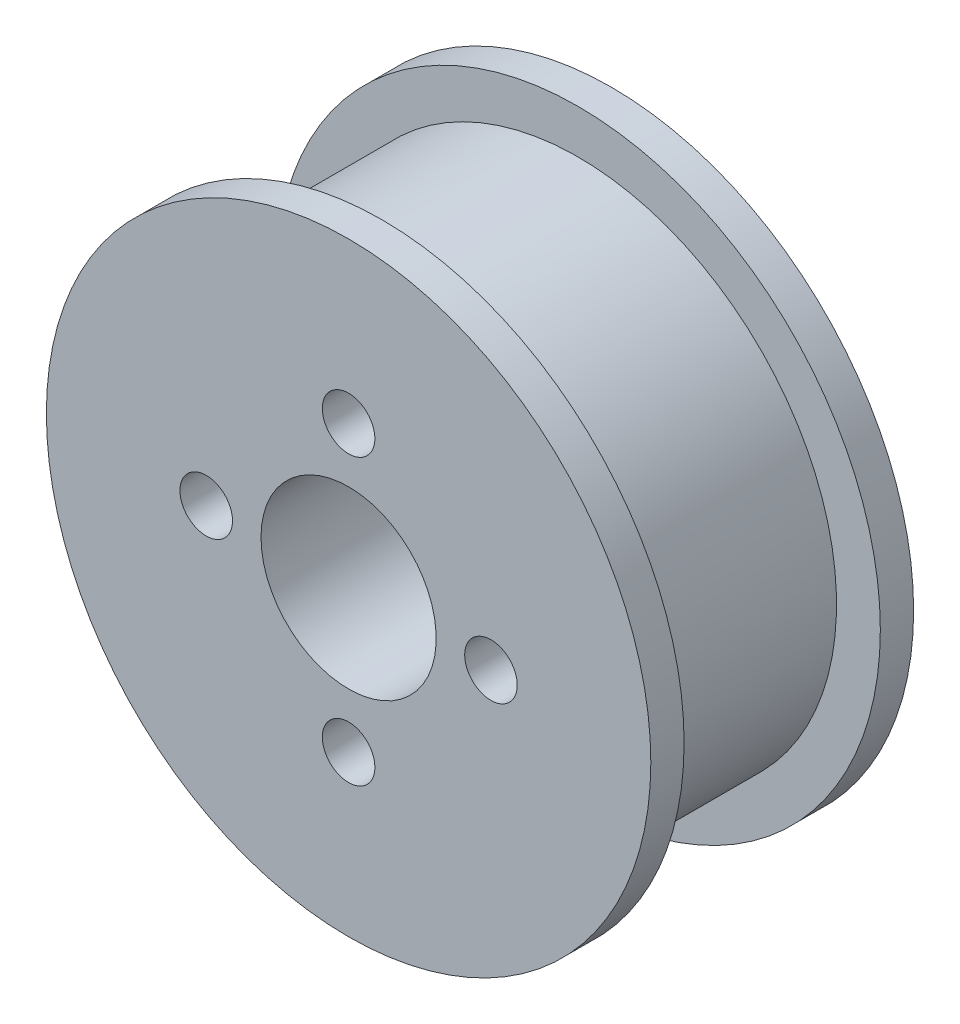
SolidWorks part; units mm, degrees
ref_plane "Front Plane" through (0, 0, 0) normal (0, 0, 1) x (1, 0, 0)
ref_plane "Top Plane" through (0, 0, 0) normal (0, 1, 0) x (1, 0, 0)
ref_plane "Right Plane" through (0, 0, 0) normal (1, 0, 0) x (0, 0, -1)
sketch "Sketch1" plane through (0, 0, 0) normal (0, 0, 1) x (1, 0, 0)
  circle A0 centre (0, 0) radius 17.25
  dimension "D1" = 34.5
extrude "Boss-Extrude1" add sketch "Sketch1" along normal blind 1.9
sketch "Sketch2" plane through (0, 0, 0) normal (0, 0, -1) x (-1, 0, 0)
  circle A0 centre (0, 0) radius 14.75
  dimension "D1" = 29.5
extrude "Boss-Extrude2" add sketch "Sketch2" along normal blind 11.2
sketch "Sketch3" plane through (0, 0, -11.2) normal (0, 0, -1) x (-1, 0, 0)
  circle A0 centre (0, 0) radius 17.25
extrude "Boss-Extrude3" add sketch "Sketch3" along normal blind 1.9
sketch "Sketch4" plane through (0, 0, -13.1) normal (0, 0, -1) x (-1, 0, 0)
  circle A0 centre (0, 0) radius 5
  dimension "D1" = 10
extrude "Cut-Extrude1" cut sketch "Sketch4" against normal through all
sketch "Sketch5" plane through (0, 0, -13.1) normal (0, 0, -1) x (-1, 0, 0)
  line L0 (0, 0) -> (8.125, 0) construction
  line L1 (0, 8.125) -> (0, 0) construction
  line L2 (0, 0) -> (-8.125, 0) construction
  line L3 (0, 0) -> (0, -8.125) construction
  circle A0 centre (0, 0) radius 11.25 construction
  circle A1 centre (0, 8.125) radius 1.5
  circle A2 centre (0, 0) radius 8.125 construction
  circle A3 centre (8.125, 0) radius 1.5
  circle A4 centre (0, -8.125) radius 1.5
  circle A5 centre (-8.125, 0) radius 1.5
  dimension "D1" = 22.5
  dimension "D2" = 16.25
  dimension "D3" = 3
extrude "Cut-Extrude2" cut sketch "Sketch5" against normal through all
